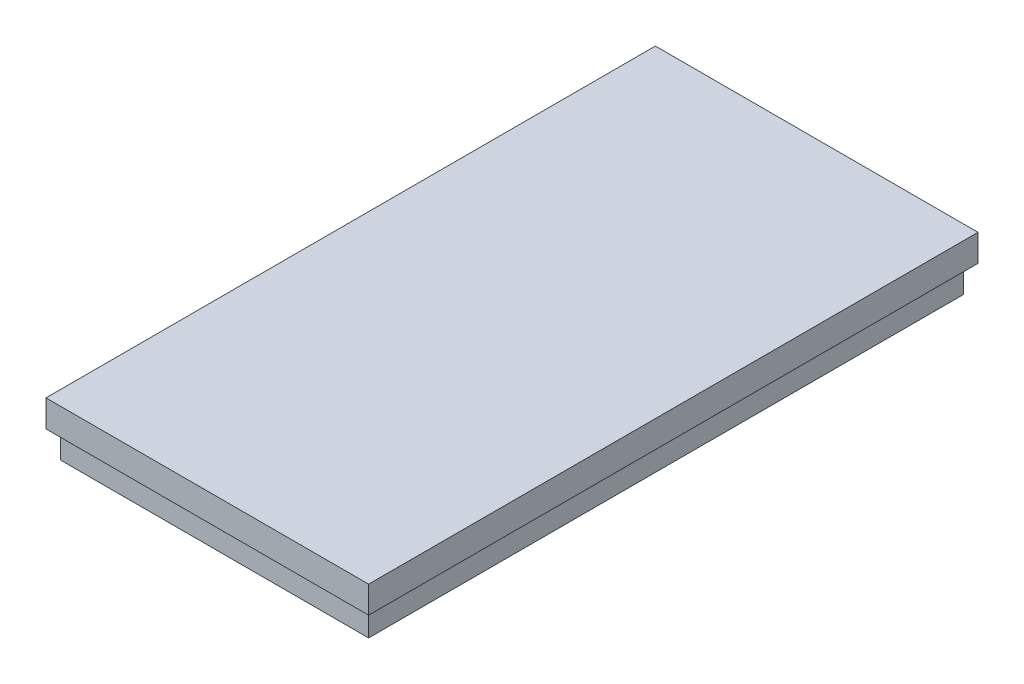
SolidWorks part; units mm, degrees
ref_plane "Front Plane" through (0, 0, 0) normal (0, 0, 1) x (1, 0, 0)
ref_plane "Top Plane" through (0, 0, 0) normal (0, 1, 0) x (1, 0, 0)
ref_plane "Right Plane" through (0, 0, 0) normal (1, 0, 0) x (0, 0, -1)
sketch "Sketch1" plane through (0, 0, 0) normal (0, 1, 0) x (1, 0, 0)
  line L0 (0, 77.55) -> (0, -82.95) construction
  line L1 (-102, 0) -> (102.9, 0) construction
  line L3 (-45, 85) -> (45, 85)
  line L4 (-45, 85) -> (-45, -85)
  line L5 (-45, -85) -> (45, -85)
  line L6 (45, 85) -> (45, -85)
  dimension "D1" = 90
  dimension "D2" = 170
extrude "Boss-Extrude1" add sketch "Sketch1" along normal blind 7.5
sketch "Sketch2" plane through (0, 0, 0) normal (0, -1, 0) x (1, 0, 0)
  line L0 (0, 77.3302) -> (0, -94.8431) construction
  line L1 (-57.3487, 0) -> (70.7024, 0) construction
  line L3 (-43, 83) -> (43, 83)
  line L4 (-43, 83) -> (-43, -83)
  line L5 (-43, -83) -> (43, -83)
  line L6 (43, 83) -> (43, -83)
  dimension "D1" = 166
  dimension "D2" = 86
extrude "Boss-Extrude2" add sketch "Sketch2" along normal blind 7.5
sketch "Sketch5" plane through (0, -7.5, 0) normal (0, -1, 0) x (1, 0, 0)
  line L0 (0, 77.5056) -> (0, -71.8944) construction
  line L1 (-33.9014, 0) -> (33.6676, 0) construction
  line L2 (-43, 83) -> (-43, -83) construction
  line L3 (-36, 76) -> (36, 76)
  line L4 (-36, 76) -> (-36, -76)
  line L5 (-36, -76) -> (36, -76)
  line L6 (36, 76) -> (36, -76)
  line L7 (43, -83) -> (43, 83) construction
  line L8 (43, 83) -> (-43, 83) construction
  line L9 (-43, -83) -> (43, -83) construction
  dimension "D1" = 7
  dimension "D2" = 7
  dimension "D3" = 7
  dimension "D4" = 7
extrude "Cut-Extrude1" cut sketch "Sketch5" against normal blind 7.5
